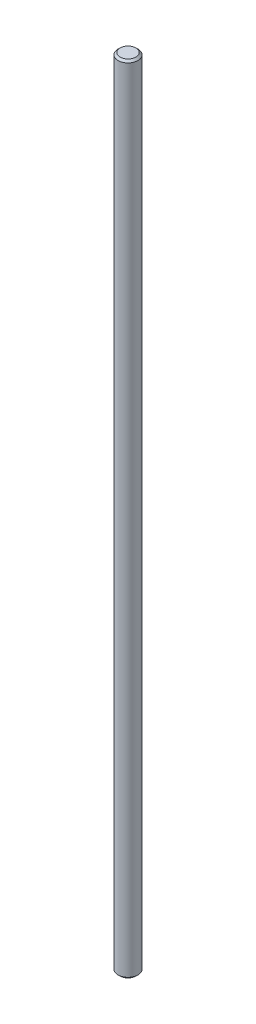
SolidWorks part; units mm, degrees
material "1.4511 (X3CrNb17)"
ref_plane "前视基准面" through (0, 0, 0) normal (0, 0, 1) x (1, 0, 0)
ref_plane "上视基准面" through (0, 0, 0) normal (0, 1, 0) x (1, 0, 0)
ref_plane "右视基准面" through (0, 0, 0) normal (1, 0, 0) x (0, 0, -1)
sketch "草图1" plane through (0, 0, 0) normal (0, 1, 0) x (1, 0, 0)
  circle A0 centre (0, 0) radius 5
  dimension "D1" = 10
extrude "凸台-拉伸1" add sketch "草图1" along normal blind 400
chamfer "倒角1" distance 1 angle 45 2 edges at (0, 0, 5) (0, 400, 5)
